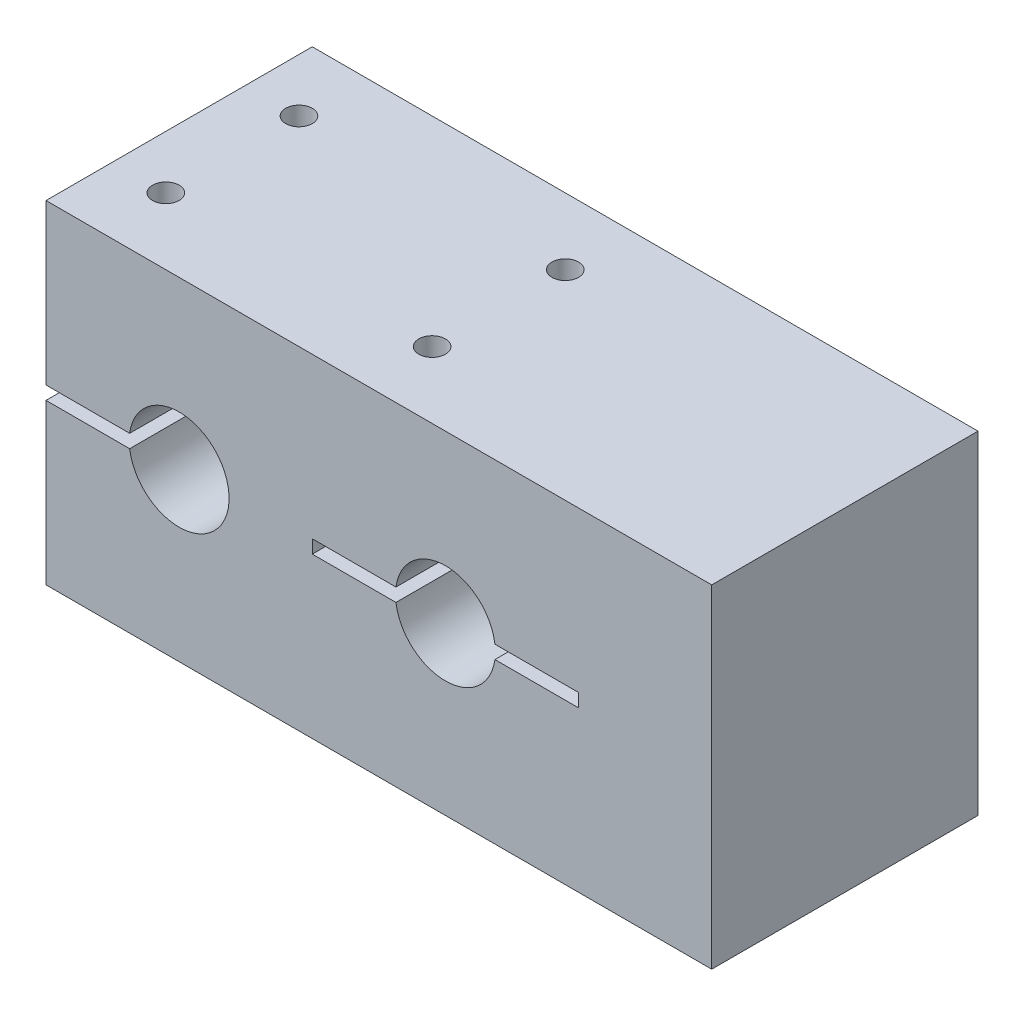
SolidWorks part; units mm, degrees
material "Сосна"
ref_plane "Спереди" through (0, 0, 0) normal (0, 0, 1) x (1, 0, 0)
ref_plane "Сверху" through (0, 0, 0) normal (0, 1, 0) x (1, 0, 0)
ref_plane "Справа" through (0, 0, 0) normal (1, 0, 0) x (0, 0, -1)
sketch "Эскиз1" plane through (0, 0, 0) normal (0, 0, 1) x (1, 0, 0)
  line L0 (52.567, 26) -> (40, 26)
  line L1 (0, 0) -> (100, 0)
  line L2 (0, 0) -> (0, 24)
  line L3 (0, 50) -> (100, 50)
  line L4 (100, 0) -> (100, 34)
  line L5 (67.433, 24) -> (80, 24)
  line L6 (0, 26) -> (12.567, 26)
  line L7 (40, 26) -> (40, 24)
  line L8 (0, 24) -> (12.567, 24)
  line L9 (0, 26) -> (0, 50)
  line L10 (40, 24) -> (52.567, 24)
  line L11 (80, 24) -> (80, 26)
  line L12 (100, 34) -> (100, 50)
  line L13 (80, 26) -> (67.433, 26)
  arc A0 (12.567, 24) -> (12.567, 26) centre (20, 25) ccw
  arc A1 (52.567, 24) -> (67.433, 24) centre (60, 25) ccw
  arc A2 (67.433, 26) -> (52.567, 26) centre (60, 25) ccw
  dimension "D5" = 40
  dimension "D4" = 25
  dimension "D10" = 7.5
  dimension "D11" = 7.5
  dimension "D12" = 7.5
  dimension "D1" = 100
  dimension "D2" = 50
  dimension "D3" = 20
  dimension "D6" = 2
  dimension "D7" = 1
  dimension "D8" = 20
  dimension "D9" = 12.567
  dimension "D13" = 20
extrude "Бобышка-Вытянуть1" add sketch "Эскиз1" along normal blind 40
sketch "Эскиз8" plane through (0, 0, 0) normal (0, -1, 0) x (1, 0, 0)
  line L0 (0, 40) -> (0, 0) construction
  line L1 (0, 40) -> (100, 40) construction
  line L2 (0, 0) -> (100, 0) construction
  circle A0 centre (8, 30) radius 2
  circle A1 centre (8, 10) radius 2
  circle A2 centre (48, 30) radius 2
  circle A3 centre (48, 10) radius 2
  dimension "D1" = 8
  dimension "D3" = 10
  dimension "D5" = 48
  dimension "D6" = 48
  dimension "D2" = 10
  dimension "D4" = 8
extrude "Вырез-Вытянуть5" cut sketch "Эскиз8" against normal blind 50
